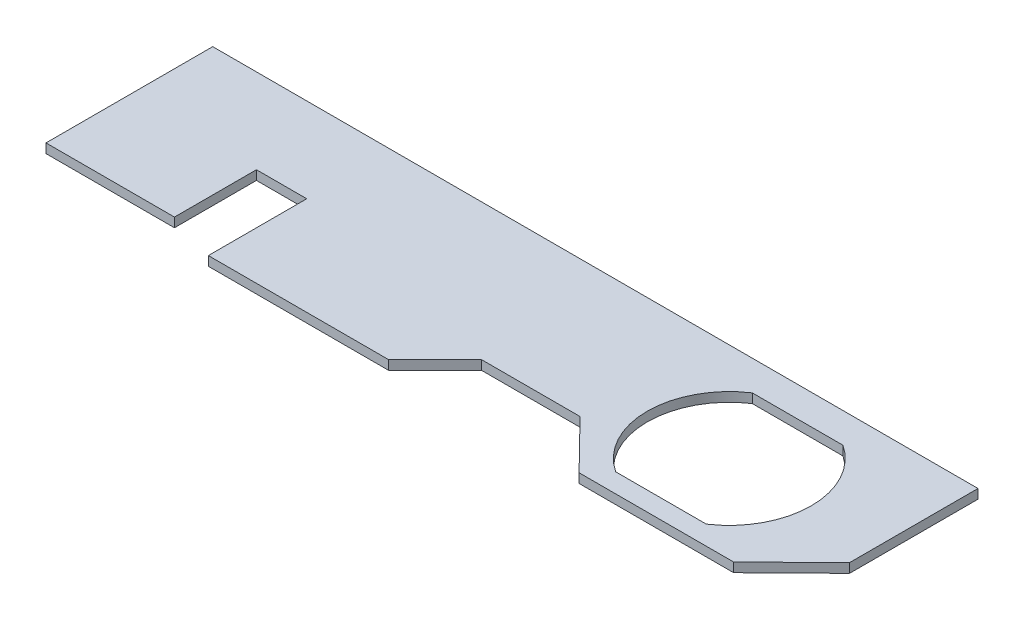
SolidWorks part; units mm, degrees
ref_plane "Front Plane" through (0, 0, 0) normal (0, 0, 1) x (1, 0, 0)
ref_plane "Top Plane" through (0, 0, 0) normal (0, 1, 0) x (1, 0, 0)
ref_plane "Right Plane" through (0, 0, 0) normal (1, 0, 0) x (0, 0, -1)
sketch "Sketch1" plane through (0, 0, 0) normal (0, 1, 0) x (1, 0, 0)
  line L0 (-31.5179, 13.9454) -> (-31.5179, -16.5546)
  line L1 (-31.5179, -16.5546) -> (-8.0179, -16.5546)
  line L2 (-8.0179, -16.5546) -> (-8.0179, -1.5546)
  line L3 (1.1821, -1.5546) -> (1.1821, -19.5546)
  line L4 (1.1821, -19.5546) -> (34.1821, -19.5546)
  line L5 (34.1821, -19.5546) -> (42.6821, -11.0546)
  line L6 (42.6821, -11.0546) -> (60.6821, -11.0546)
  line L7 (60.6821, -11.0546) -> (69.5038, -20.0546)
  line L8 (69.5038, -20.0546) -> (97.7699, -20.0546)
  line L9 (97.7699, -20.0546) -> (108.4821, -9.5546)
  line L10 (108.4821, -9.5546) -> (108.4821, 13.9454)
  line L11 (108.4821, 13.9454) -> (-31.5179, 13.9454)
  line L12 (-8.0179, -1.5546) -> (1.1821, -1.5546)
  line L13 (89.2736, 8.4454) -> (72.6905, 8.4454)
  line L14 (89.2736, -16.5546) -> (72.6905, -16.5546)
  arc A1 (89.2736, -16.5546) -> (89.2736, 8.4454) centre (80.9821, -4.0546) ccw
  arc A2 (72.6905, 8.4454) -> (72.6905, -16.5546) centre (80.9821, -4.0546) ccw
  point P20 (80.9821, -4.0546)
  dimension "D15" = 140
  dimension "D1" = 30.5
  dimension "D2" = 23.5
  dimension "D3" = 15
  dimension "D4" = 9.2
  dimension "D5" = 33.5
  dimension "D6" = 25
  dimension "D7" = 34
  dimension "D8" = 15
  dimension "D9" = 23.5
  dimension "D10" = 33
  dimension "D11" = 41.5
  dimension "D12" = 18
  dimension "D13" = 5.5
  dimension "D14" = 3.5
extrude "Boss-Extrude1" add sketch "Sketch1" along normal blind 1.7 contours L2 L12 L3 L4 L5 L6 L7 L8 L9 L10 L11 L0 L1 A2 L13 A1 L14
fillet "Fillet1" [suppressed] radius 1.5
